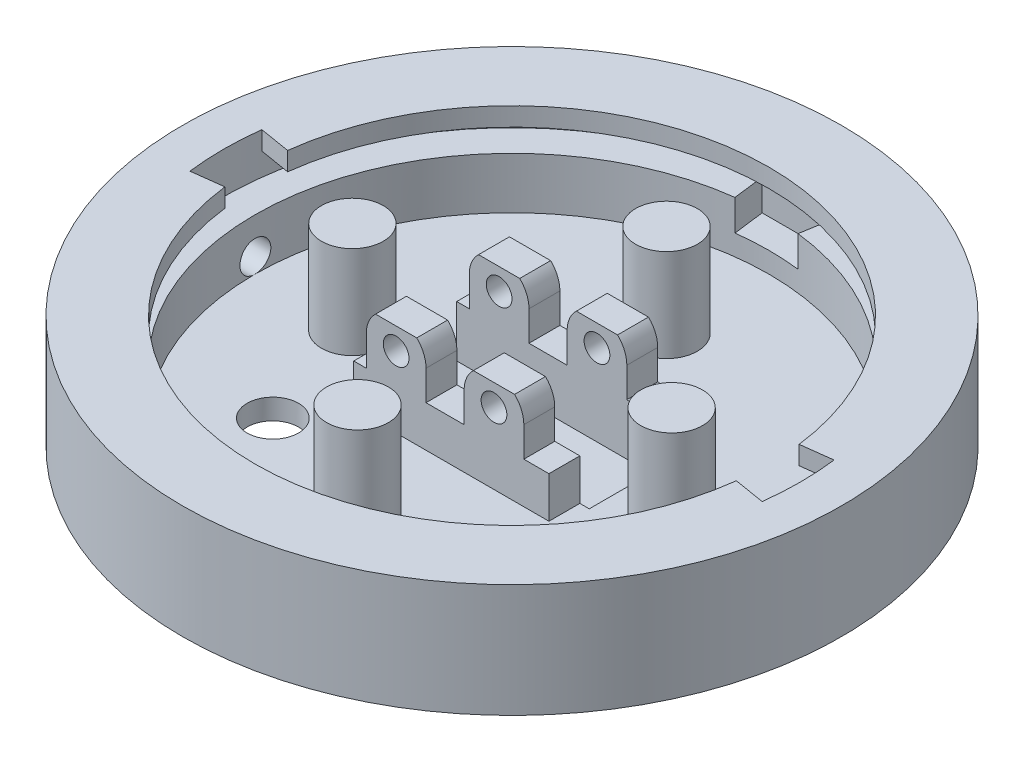
SolidWorks part; units mm, degrees
ref_plane "Front Plane" through (0, 0, 0) normal (0, 0, 1) x (1, 0, 0)
ref_plane "Top Plane" through (0, 0, 0) normal (0, 1, 0) x (1, 0, 0)
ref_plane "Right Plane" through (0, 0, 0) normal (1, 0, 0) x (0, 0, -1)
sketch "Sketch1" plane through (0, 0, 0) normal (0, 1, 0) x (1, 0, 0)
  circle A0 centre (0, 0) radius 30
extrude "Boss-Extrude1" add sketch "Sketch1" along normal blind 20
sketch "Sketch2" plane through (0, 20, 0) normal (0, 1, 0) x (1, 0, 0)
  circle A0 centre (0, 0) radius 28
extrude "Cut-Extrude1" cut sketch "Sketch2" against normal blind 10
sketch "Sketch3" plane through (0, 10, 0) normal (0, 1, 0) x (1, 0, 0)
  line L0 (0, 0) -> (0, -3.5)
  line L1 (0, 0) -> (0, 3.5)
  line L2 (0, 3.5) -> (11, 3.5)
  line L3 (11, 3.5) -> (11, -3.5)
  line L4 (11, -3.5) -> (-11, -3.5)
  line L5 (-11, -3.5) -> (-11, 3.5)
  line L6 (-11, 3.5) -> (0, 3.5)
extrude "Cut-Extrude2" cut sketch "Sketch3" against normal blind 5 and the other way blind 6.5 contours L6 L5 L4 L0 L1 | L4 L3 L2 L1 L0
sketch "Sketch4" plane through (0, 0, 0) normal (0, 0, 1) x (1, 0, 0)
  line L0 (0, 0) -> (0, 5)
  line L1 (0, -11) -> (0, 11) construction
  line L2 (-7.65, 10) -> (-4.75, 10)
  line L3 (1.85, 10) -> (7.65, 10)
  line L7 (-7.65, 12.9) -> (-7.65, 10)
  line L8 (-1.85, 12.9) -> (-1.85, 10)
  line L9 (7.65, 12.9) -> (7.65, 10)
  line L10 (-4.75, 10) -> (-1.85, 10)
  line L11 (1.85, 12.9) -> (1.85, 10)
  circle A0 centre (-4.75, 12.9) radius 1.25
  circle A1 centre (4.75, 12.9) radius 1.25
  arc A2 (-1.85, 12.9) -> (-7.65, 12.9) centre (-4.75, 12.9) ccw
  arc A3 (7.65, 12.9) -> (1.85, 12.9) centre (4.75, 12.9) ccw
  dimension "D2" = 2.9
extrude "Boss-Extrude2" add sketch "Sketch4" along normal blind 6.5 and the other way blind 6.5 contours L8 A2 L7 L2 L10 A0 | L9 A3 L11 L3 A1
sketch "Sketch5" plane through (0, 10, 0) normal (0, 1, 0) x (1, 0, 0)
  line L0 (-11, 3.5) -> (11, 3.5)
  line L1 (11, 3.5) -> (11, -3.5)
  line L2 (11, -3.5) -> (-11, -3.5) construction
  line L3 (11, -3.5) -> (11, 3.5) construction
  line L4 (11, -3.5) -> (-11, -3.5)
  line L5 (-11, -3.5) -> (-11, 3.5)
extrude "Cut-Extrude4" cut sketch "Sketch5" along normal blind 8.5
sketch "Sketch6" plane through (0, 0, 0) normal (0, 0, 1) x (1, 0, 0)
  circle A0 centre (0, 17.5) radius 1
sketch "Sketch8" plane through (0, 10, 0) normal (0, 1, 0) x (1, 0, 0)
  circle A0 centre (0, 15) radius 3
  circle A1 centre (0, -15) radius 3
extrude "Boss-Extrude3" add sketch "Sketch8" along normal blind 10
sketch "Sketch9" plane through (0, 0, 0) normal (0, -1, 0) x (1, 0, 0)
  circle A0 centre (0, 0) radius 30
extrude "Cut-Extrude6" cut sketch "Sketch9" against normal blind 4
sketch "Sketch11" plane through (0, 20, 0) normal (0, 1, 0) x (1, 0, 0)
  line L0 (-27.7813, -3.4932) -> (-27.7813, 3.4932)
  line L1 (27.7812, -3.4932) -> (27.7813, 3.4932)
  line L3 (-24.7665, -3.1141) -> (-27.7813, -3.4932)
  line L4 (-24.7812, 2.9941) -> (-27.7813, 3.4932)
  line L5 (24.7665, 3.1141) -> (27.7813, 3.4932)
  line L6 (24.7812, -2.9941) -> (27.7812, -3.4932)
  line L7 (24.954, 0.1199) -> (24.7812, -2.9941)
  line L8 (24.954, 0.1199) -> (24.7665, 3.1141)
  circle A0 centre (0, 0) radius 30
  arc A1 (-24.7665, -3.1141) -> (-24.7812, 2.9941) centre (0, 0) ccw
  circle A2 centre (0, 0) radius 28 construction
  circle A3 centre (0, 0) radius 24.9615
  point P20 (0, 0)
  circle M8 centre (0, 0) radius 28
  dimension "D1" = 2
  dimension "D2" = 3
extrude "Boss-Extrude4" add sketch "Sketch11" against normal blind 7 separate body contours A1 L3 L6 M8 | A1 L5 L4 M8
sketch "Sketch12" plane through (0, 20, 0) normal (0, 1, 0) x (1, 0, 0)
  circle A0 centre (0, 0) radius 30
extrude "Cut-Extrude7" cut sketch "Sketch12" against normal blind 5
sketch "Sketch13" plane through (0, 10, 0) normal (0, 1, 0) x (1, 0, 0)
  circle A0 centre (0, 0) radius 12
  circle A1 centre (0, 0) radius 28
extrude "Cut-Extrude8" cut sketch "Sketch13" against normal blind 4
sketch "Sketch16" plane through (0, 15, 0) normal (0, 1, 0) x (1, 0, 0)
  line L0 (-27.7813, -3.4932) -> (-24.7665, -3.1141)
  line L1 (-27.7813, 3.4932) -> (-24.7812, 2.9941)
  line L2 (24.7812, -2.9941) -> (27.7812, -3.4932)
  line L3 (24.7665, 3.1141) -> (27.7813, 3.4932)
  circle A0 centre (0, 0) radius 28 construction
  circle A1 centre (0, 0) radius 28 construction
  arc A2 (24.7665, 3.1141) -> (-24.7812, 2.9941) centre (0, 0) ccw
  arc A3 (27.7813, 3.4932) -> (-27.7813, 3.4932) centre (0, 0) ccw
  arc A4 (-24.7665, -3.1141) -> (24.7812, -2.9941) centre (0, 0) ccw
  arc A5 (-27.7813, -3.4932) -> (27.7812, -3.4932) centre (0, 0) ccw
extrude "Boss-Extrude5" add sketch "Sketch16" against normal blind 9
ref_plane "Plane1" through (0, 11, 0) normal (0, 1, 0) x (1, 0, 0)
sketch "Sketch17" plane through (0, 11, 0) normal (0, 1, 0) x (1, 0, 0)
  circle A0 centre (0, 0) radius 26.48
sketch "Sketch24" plane through (0, 0, 0) normal (0, 0, 1) x (1, 0, 0)
  line L10 (-28, 11) -> (-28, 13.2)
  line L11 (-28, 13.2) -> (-23.5808, 13.2)
  line L12 (-23.5808, 13.2) -> (-23.5808, 11)
  line L13 (-23.5808, 11) -> (-28, 11)
  dimension "D1" = 2.2
sweep "Cut-Sweep2" cut profiles "Sketch24" path "Sketch17"
sketch "Sketch15" plane through (0, 10, 0) normal (0, 1, 0) x (1, 0, 0)
  line L0 (-7.65, 6.5) -> (-10.0871, 6.5)
  line L1 (-10.0871, 6.5) -> (10.0871, 6.5)
  line L2 (-7.65, -6.5) -> (-10.0871, -6.5)
  line L3 (-10.0871, -6.5) -> (10.0871, -6.5)
  arc A0 (-10.0871, -6.5) -> (10.0871, -6.5) centre (0, 0) ccw
  arc A1 (10.0871, 6.5) -> (-10.0871, 6.5) centre (0, 0) ccw
  line M2 (1.85, 6.5) -> (7.65, 6.5)
  line M8 (7.65, -6.5) -> (1.85, -6.5)
  line M12 (-1.85, -6.5) -> (-7.65, -6.5)
  line M18 (-7.65, 6.5) -> (-1.85, 6.5)
  circle M22 centre (0, 0) radius 12
extrude "Cut-Extrude9" cut sketch "Sketch15" against normal blind 4 contours L3 L2 M12 M22 M8 | L1 L0 M18 M2 M22
sketch "Sketch32" plane through (0, 11, 0) normal (0, 1, 0) x (1, 0, 0)
  line L4 (3.1141, -24.7665) -> (-2.9941, -24.7812)
  line L5 (3.4932, -27.7813) -> (3.1141, -24.7665)
  line L6 (-3.4932, -27.7812) -> (3.4932, -27.7813)
  line L7 (-2.9941, -24.7812) -> (-3.4932, -27.7812)
  line L12 (-3.1141, 24.7665) -> (2.9941, 24.7812)
  line L13 (-3.4932, 27.7813) -> (-3.1141, 24.7665)
  line L14 (3.4932, 27.7812) -> (-3.4932, 27.7813)
  line L15 (2.9941, 24.7812) -> (3.4932, 27.7812)
  point P23 (0, 0)
extrude "Cut-Extrude10" cut sketch "Sketch32" against normal blind 3
sketch "Sketch33" plane through (0, 11, 0) normal (0, 1, 0) x (1, 0, 0)
  line L0 (-24.7812, 2.9941) -> (-27.7813, 3.4932)
  line L2 (-27.7812, -3.4932) -> (-24.7665, -3.1141)
  line L3 (24.7665, 3.1141) -> (27.7813, 3.4932)
  line L4 (24.7812, -2.9941) -> (27.7812, -3.4932)
  arc A0 (27.7812, -3.4932) -> (27.7813, 3.4932) centre (0, 0) ccw
  arc A1 (24.7812, -2.9941) -> (24.7665, 3.1141) centre (0, 0) ccw
  arc A2 (-24.7812, 2.9941) -> (-24.7665, -3.1141) centre (0, 0) ccw
  arc A3 (-27.7813, 3.4932) -> (-27.7812, -3.4932) centre (0, 0) ccw
extrude "Boss-Extrude6" add sketch "Sketch33" against normal blind 5
sketch "Sketch34" plane through (0, 15, 0) normal (0, 1, 0) x (1, 0, 0)
  circle A1 centre (0, 15) radius 3
  circle A2 centre (0, -15) radius 3
extrude "Boss-Extrude7" add sketch "Sketch34" against normal blind 9
sketch "Sketch35" plane through (-11, 0, 0) normal (1, 0, 0) x (0, 0, -1)
  circle A0 centre (0, 7.5) radius 1.5
extrude "Cut-Extrude12" cut sketch "Sketch35" against normal blind 41 and the other way blind 53
sketch "Sketch37" plane through (0, 6, 0) normal (0, 1, 0) x (1, 0, 0)
  line L0 (0, 0) -> (-15.5, 0)
  line L1 (0, 0) -> (15.5, 0)
  circle A1 centre (-15.5, 0) radius 3
  circle A2 centre (15.5, 0) radius 3
extrude "Boss-Extrude9" add sketch "Sketch37" along normal blind 9 contours A1 | A2
sketch "Sketch38" plane through (0, 6, 0) normal (0, 1, 0) x (1, 0, 0)
  circle A0 centre (-11.9886, -11.2343) radius 2.5
extrude "Cut-Extrude13" cut sketch "Sketch38" against normal blind 10
sketch "Sketch39" plane through (0, 6, 0) normal (0, 1, 0) x (1, 0, 0)
  line L0 (-8.8686, -6.5) -> (-8.8686, 6.5)
  line L1 (-10.0871, -6.5) -> (-7.65, -6.5) construction
  line L2 (-10.0871, 6.5) -> (-7.65, 6.5) construction
  line L3 (-8.8686, 6.5) -> (-11.5934, 6.5)
  line L5 (-11.5934, -6.5) -> (-8.8686, -6.5)
  line L6 (-12, 0) -> (-12, 6.5)
  line L7 (-12, 6.5) -> (-11.5934, 6.5)
  line L8 (-12, 0) -> (-12, -6.5)
  line L9 (-12, -6.5) -> (-11.5934, -6.5)
  line L10 (10.0871, -6.5) -> (10.0871, 6.5)
  line L11 (10.0871, 6.5) -> (12.3182, 6.5)
  line L13 (12.3182, -6.5) -> (10.0871, -6.5)
  line L14 (10.0871, -6.5) -> (12.3182, -6.5)
  line L15 (12.3182, 6.5) -> (12.3182, -6.5)
  arc M11 (-10.0871, -6.5) -> (-12, 0) centre (0, 0) cw
  arc M12 (-12, 0) -> (-10.0871, 6.5) centre (0, 0) cw
  line M13 (-10.0871, 6.5) -> (10.0871, 6.5)
  arc M14 (10.0871, 6.5) -> (12, 0) centre (0, 0) cw
  arc M15 (12, 0) -> (10.0871, -6.5) centre (0, 0) cw
  line M16 (10.0871, -6.5) -> (-10.0871, -6.5)
extrude "Cut-Extrude14" cut sketch "Sketch39" along normal blind 5 contours L15 L11 L13 M14 M15 | L0 M16 M13 M12 M11 | L8 L9 L5 M11
sketch "Sketch40" plane through (0, 10, 0) normal (0, 1, 0) x (1, 0, 0)
  line L0 (10.0871, -6.5) -> (10.0871, 6.5)
  line L1 (10.0871, 6.5) -> (12.749, 6.5)
  line L2 (12.749, 6.5) -> (12.749, -6.5)
  line L3 (12.749, -6.5) -> (10.0871, -6.5)
sketch "Sketch41" plane through (0, 6, 0) normal (0, 1, 0) x (1, 0, 0)
  line L0 (10.0871, 6.5) -> (10.0871, -6.5)
  line L1 (10.0871, -6.5) -> (12.0871, -6.5)
  line L2 (12.0871, -6.5) -> (12.0871, 6.5)
  line L3 (12.0871, 6.5) -> (10.0871, 6.5)
extrude "Cut-Extrude17" cut sketch "Sketch41" along normal blind 5 contours L3 L0 L1 L2
sketch "Sketch43" plane through (0, 4, 0) normal (0, -1, 0) x (-1, 0, 0)
  circle A0 centre (0, 0) radius 30
  circle A1 centre (0, 0) radius 32
extrude "Boss-Extrude10" add sketch "Sketch43" against normal blind 11
